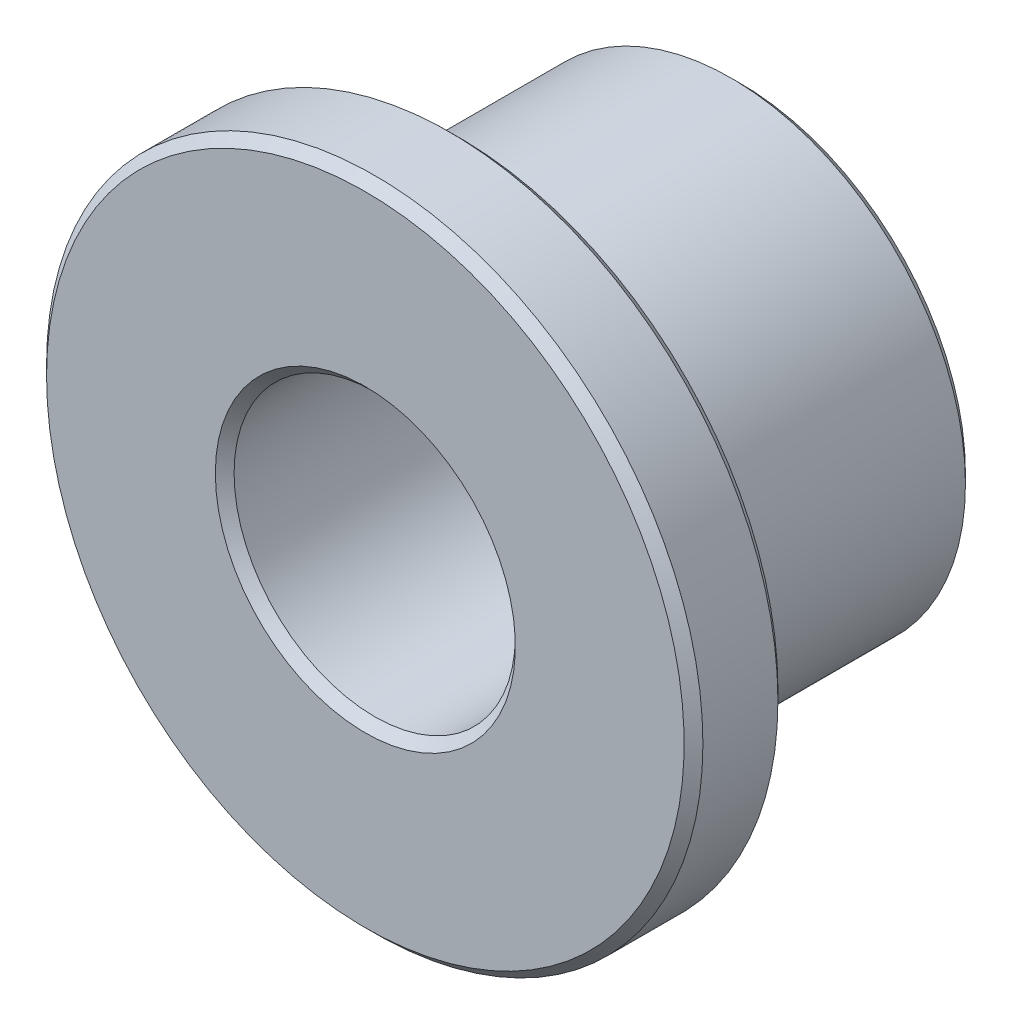
SolidWorks part; units mm, degrees
material "铜"
ref_plane "前视基准面" through (0, 0, 0) normal (0, 0, 1) x (1, 0, 0)
ref_plane "上视基准面" through (0, 0, 0) normal (0, 1, 0) x (1, 0, 0)
ref_plane "右视基准面" through (0, 0, 0) normal (1, 0, 0) x (0, 0, -1)
sketch "Sketch1" plane through (0, 0, 0) normal (1, 0, 0) x (0, 0, -1)
  line L0 (0, 3) -> (0, 7)
  line L1 (0, 7) -> (2, 7)
  line L2 (2, 7) -> (2, 5)
  line L3 (2, 5) -> (8, 5)
  line L4 (8, 5) -> (8, 3)
  line L5 (8, 3) -> (0, 3)
  line L6 (0, 0) -> (10.5659, 0) construction
  dimension "D1" = 3
  dimension "D2" = 5
  dimension "D3" = 8
  dimension "D4" = 2
  dimension "D5" = 7
revolve "Revolve1" add sketch "Sketch1" angle 360 about L6
chamfer "Chamfer1" distance 0.2 angle 45 6 edges at (7, 0, -2) (7, 0, 0) (5, 0, -8) (5, 0, -2) (3, 0, 0) (3, 0, -8)
